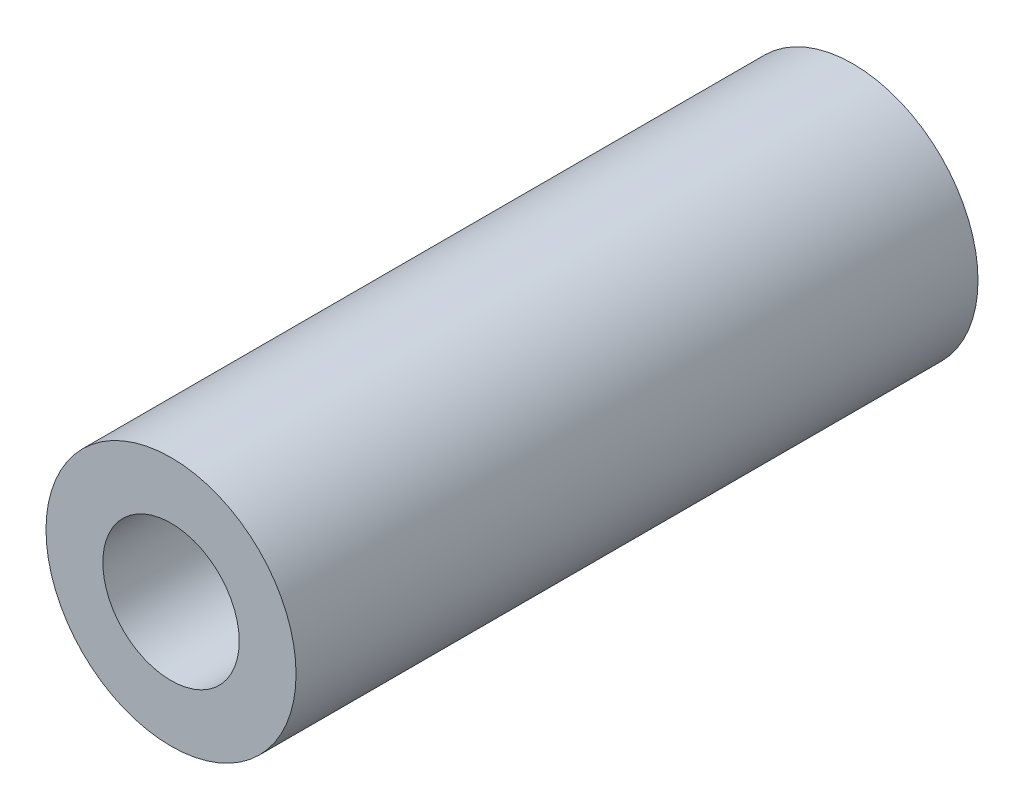
SolidWorks part; units mm, degrees
ref_plane "Front Plane" through (0, 0, 0) normal (0, 0, 1) x (1, 0, 0)
ref_plane "Top Plane" through (0, 0, 0) normal (0, 1, 0) x (1, 0, 0)
ref_plane "Right Plane" through (0, 0, 0) normal (1, 0, 0) x (0, 0, -1)
sketch "Spout Sketch" plane through (0, 0, 0) normal (0, 0, 1) x (1, 0, 0)
  circle A0 centre (0, 0) radius 11
  circle A1 centre (0, 0) radius 6
  dimension "D1" = 22
  dimension "D2" = 12
extrude "Spout" add sketch "Spout Sketch" along normal blind 60
